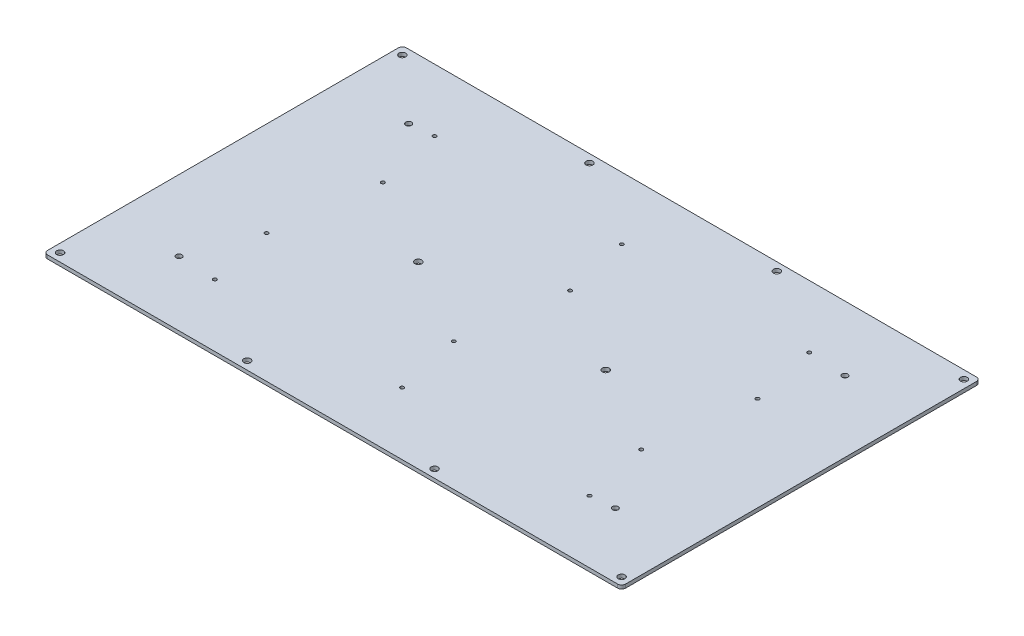
SolidWorks part; units mm, degrees
material "1060 Alloy"
ref_plane "Front" through (0, 0, 0) normal (0, 0, 1) x (1, 0, 0)
ref_plane "Top" through (0, 0, 0) normal (0, 1, 0) x (1, 0, 0)
ref_plane "Right" through (0, 0, 0) normal (1, 0, 0) x (0, 0, -1)
sketch "Sketch1" plane through (0, 0, 0) normal (0, 1, 0) x (1, 0, 0)
  line L1 (-184.15, -114.3) -> (184.15, -114.3)
  line L2 (-184.15, -114.3) -> (-184.15, 114.3)
  line L3 (-184.15, 114.3) -> (184.15, 114.3)
  line L4 (184.15, -114.3) -> (184.15, 114.3)
  line L5 (-184.15, -114.3) -> (184.15, 114.3) construction
  line L6 (-184.15, 114.3) -> (184.15, -114.3) construction
  point P0 (0, 0)
  dimension "D1" = 368.3
  dimension "D2" = 228.6
extrude "Boss-Extrude1" add sketch "Sketch1" along normal blind 2.286
hole_wizard "#6 Clearance Hole1" positions "Sketch2" profile "Sketch3" hole size "#6" standard "ANSI Inch" end condition through all
sketch "Sketch2" plane through (0, 0, 0) normal (0, -1, 0) x (-1, 0, 0)
  point P0 (-139.0015, 73.152)
  point P3 (139.0015, 73.152)
  point P6 (139.0015, -73.152)
  point P9 (-139.0015, -73.152)
sketch "Sketch3" plane through (139.0015, 0, -73.152) normal (1, 0, 0) x (0, 0, -1)
  line L0 (0, 0) -> (0, 2.286)
  line L1 (0, 2.286) -> (1.8288, 2.286)
  line L2 (1.8288, 2.286) -> (1.8288, 0)
  line L5 (1.8288, 0) -> (0, 0)
  line L11 (0, -6.35) -> (0, 107.95) construction
  dimension "Thru Hole Dia." = 3.6576
  dimension "Thru Hole Depth" = 2.286
hole_wizard "Tap Drill for #4-40 Tap1" positions "Sketch4" profile "Sketch5" hole size "#4-40" standard "ANSI Inch" end condition through all
sketch "Sketch4" plane through (0, 0, 0) normal (0, -1, 0) x (-1, 0, 0)
  point P0 (-114.8474, 74.5473)
  point P3 (-123.9126, 32.5137)
  point P6 (4.5326, 74.5473)
  point P9 (-4.5326, 32.5137)
  point P12 (123.9126, 74.5473)
  point P15 (114.8474, 32.5137)
  point P18 (123.9126, -32.5137)
  point P21 (114.8474, -74.5473)
  point P24 (4.5326, -32.5137)
  point P27 (-4.5326, -74.5473)
  point P30 (-114.8474, -32.5137)
  point P33 (-123.9126, -74.5473)
sketch "Sketch5" plane through (114.8474, 0, -74.5473) normal (1, 0, 0) x (0, 0, -1)
  line L0 (0, 0) -> (0, 2.286)
  line L1 (0, 2.286) -> (1.1303, 2.286)
  line L2 (1.1303, 2.286) -> (1.1303, 0)
  line L5 (1.1303, 0) -> (0, 0)
  line L11 (0, -6.35) -> (0, 107.95) construction
  dimension "Thru Hole Dia." = 2.2606
  dimension "Thru Hole Depth" = 2.286
fillet "Fillet1" radius 2.54 4 edges at (184.15, 1.143, -114.3) (-184.15, 1.143, -114.3) (-184.15, 1.143, 114.3) (184.15, 1.143, 114.3)
hole_wizard "#8 Clearance Hole1" positions "Sketch6" profile "Sketch7" hole size "#8" standard "ANSI Inch" end condition through all
sketch "Sketch6" plane through (0, 0, 0) normal (0, -1, 0) x (-1, 0, 0)
  line L0 (-184.15, 109.0578) -> (184.15, 109.0578) construction
  line L1 (-184.15, -111.76) -> (-184.15, 111.76) construction
  line L2 (184.15, 111.76) -> (184.15, -111.76) construction
  line L4 (0, 103.8155) -> (0, 114.3) construction
  line L5 (24.1534, 103.8155) -> (-24.1534, 103.8155) construction
  line L6 (-181.61, 114.3) -> (181.61, 114.3) construction
  line L8 (0, -103.8155) -> (0, -114.3) construction
  line L9 (-24.1534, -103.8155) -> (24.1534, -103.8155) construction
  line L10 (181.61, -114.3) -> (-181.61, -114.3) construction
  line L13 (-178.9078, 109.0578) -> (178.9078, 109.0578) construction
  line L14 (-178.9078, 109.0578) -> (-178.9078, -109.0578) construction
  line L15 (-178.9078, -109.0578) -> (178.9078, -109.0578) construction
  line L16 (178.9078, 109.0578) -> (178.9078, -109.0578) construction
  line L18 (-119.38, -53.5305) -> (0, -53.5305) construction
  line L20 (0, -53.5305) -> (119.38, -53.5305) construction
  line L22 (-59.69, -53.5305) -> (-59.69, -109.0578) construction
  line L23 (-59.69, -53.5305) -> (-59.69, 109.0578) construction
  line L24 (59.69, -53.5305) -> (59.69, -109.0578) construction
  line L25 (59.69, -53.5305) -> (59.69, 109.0578) construction
  line L26 (178.9078, 109.0578) -> (178.9078, 114.3) construction
  line L28 (178.9078, 107.95) -> (184.15, 107.95) construction
  point P16 (0, 109.0578)
  point P25 (-178.9078, 109.0578)
  point P26 (178.9078, -109.0578)
  point P215 (-178.9078, -109.0578)
  point P216 (178.9078, 109.0578)
  point P218 (0, -109.0578)
  point P219 (0, -109.0578)
  point P250 (-59.69, -109.0578)
  point P253 (-59.69, 109.0578)
  point P255 (59.69, -109.0578)
  point P257 (59.69, 109.0578)
  point P282 (-59.69, 0)
  point P285 (59.69, 0)
  dimension "D1" = 6.35
sketch "Sketch7" plane through (-59.69, 0, 0) normal (1, 0, 0) x (0, 0, -1)
  line L0 (0, 0) -> (0, 2.286)
  line L1 (0, 2.286) -> (2.1526, 2.286)
  line L2 (2.1526, 2.286) -> (2.1526, 0)
  line L5 (2.1526, 0) -> (0, 0)
  line L11 (0, -6.35) -> (0, 107.95) construction
  dimension "Thru Hole Dia." = 4.3053
  dimension "Thru Hole Depth" = 2.286
